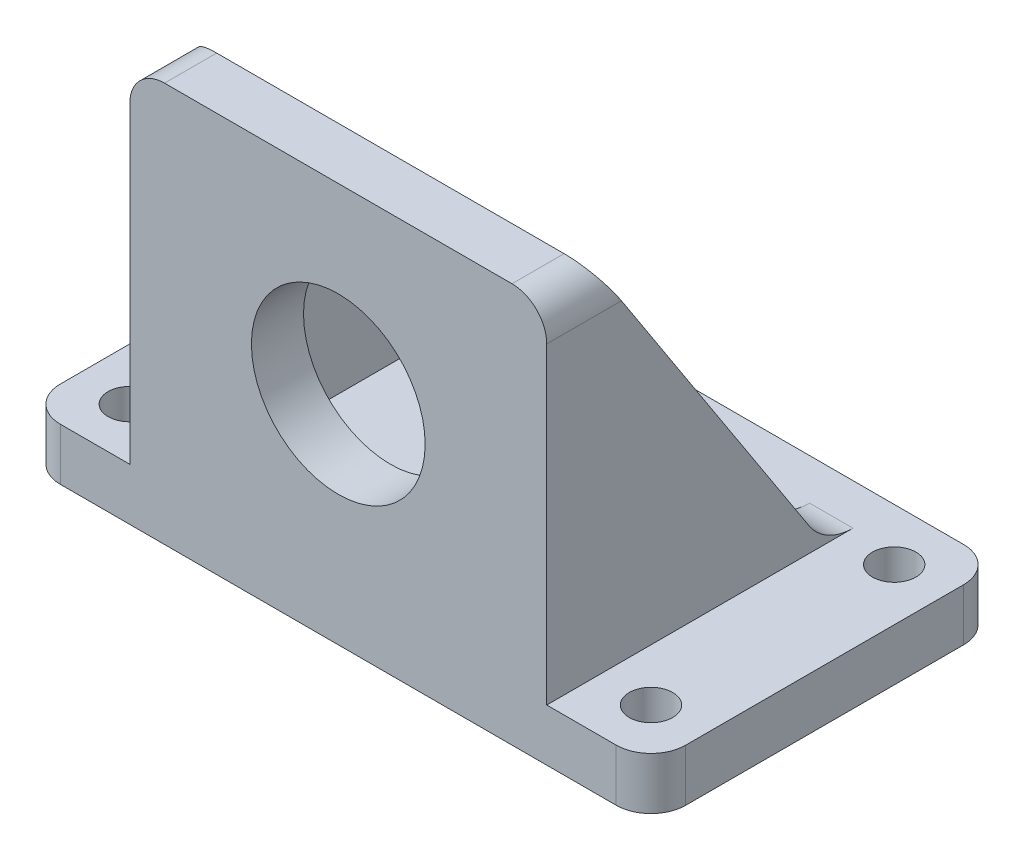
SolidWorks part; units mm, degrees
material "6061-T6 (SS)"
ref_plane "前视基准面" through (0, 0, 0) normal (0, 0, 1) x (1, 0, 0)
ref_plane "上视基准面" through (0, 0, 0) normal (0, 1, 0) x (1, 0, 0)
ref_plane "右视基准面" through (0, 0, 0) normal (1, 0, 0) x (0, 0, -1)
sketch "草图1" plane through (0, 0, 0) normal (0, 1, 0) x (1, 0, 0)
  line L1 (0, 0) -> (36, 0)
  line L2 (0, 0) -> (0, 20)
  line L3 (0, 20) -> (36, 20)
  line L4 (36, 0) -> (36, 20)
  dimension "D1" = 20
  dimension "D2" = 36
extrude "凸台-拉伸1" add sketch "草图1" along normal blind 3
sketch "草图6" plane through (0, 3, 0) normal (0, 1, 0) x (1, 0, 0)
  line L0 (0, 10) -> (36, 10) construction
  line L1 (0, 20) -> (0, 0) construction
  line L2 (36, 0) -> (36, 20) construction
  line L4 (3, 17) -> (33, 17) construction
  line L5 (3, 17) -> (3, 3) construction
  line L6 (3, 3) -> (33, 3) construction
  line L7 (33, 17) -> (33, 3) construction
  line L8 (3, 17) -> (33, 3) construction
  line L9 (3, 3) -> (33, 17) construction
  circle A0 centre (3, 3) radius 1.25
  circle A1 centre (3, 17) radius 1.25
  circle A2 centre (33, 17) radius 1.25
  circle A3 centre (33, 3) radius 1.25
  point P6 (18, 10)
  dimension "D1" = 2.5
  dimension "D2" = 30
  dimension "D3" = 14
extrude "切除-拉伸3" cut sketch "草图6" against normal through all
sketch "草图2" plane through (0, 3, 0) normal (0, 1, 0) x (1, 0, 0)
  line L0 (0, 0) -> (36, 0) construction
  line L1 (6, 0) -> (30, 0)
  line L2 (6, 0) -> (6, 16)
  line L3 (6, 16) -> (8.5, 16)
  line L4 (30, 0) -> (30, 16)
  line L5 (18, 20) -> (18, 16) construction
  line L6 (36, 20) -> (0, 20) construction
  line L7 (8.5, 16) -> (8.5, 3)
  line L8 (8.5, 3) -> (27.5, 3)
  line L9 (27.5, 3) -> (27.5, 16)
  line L10 (8.5, 16) -> (27.5, 16) construction
  line L11 (27.5, 16) -> (30, 16)
  dimension "D1" = 24
  dimension "D2" = 4
  dimension "D3" = 3
  dimension "D4" = 2.5
extrude "凸台-拉伸2" add sketch "草图2" along normal blind 20
sketch "草图3" plane through (0, 0, 0) normal (0, 0, 1) x (1, 0, 0)
  line L0 (18, 23) -> (18, 0) construction
  line L1 (6, 23) -> (30, 23) construction
  line L2 (0, 0) -> (36, 0) construction
  circle A0 centre (18, 12.5) radius 5
  dimension "D1" = 12.5
  dimension "D2" = 10
extrude "切除-拉伸1" cut sketch "草图3" against normal up to next
sketch "草图4" plane through (30, 0, 0) normal (1, 0, 0) x (0, 0, -1)
  line L0 (3, 23) -> (16, 23)
  line L1 (16, 23) -> (16, 3)
  line L2 (16, 3) -> (3, 23)
extrude "切除-拉伸2" cut sketch "草图4" against normal through all
fillet "圆角1" radius 2 4 edges at (0, 1.5, -20) (0, 1.5, 0) (36, 1.5, 0) (36, 1.5, -20)
fillet "圆角2" [suppressed] radius 1
fillet "圆角3" radius 3 2 edges at (7.25, 3, -16) (28.75, 3, -16)
fillet "圆角4" radius 2 2 edges at (6, 23, -1.5) (30, 23, -1.5)
